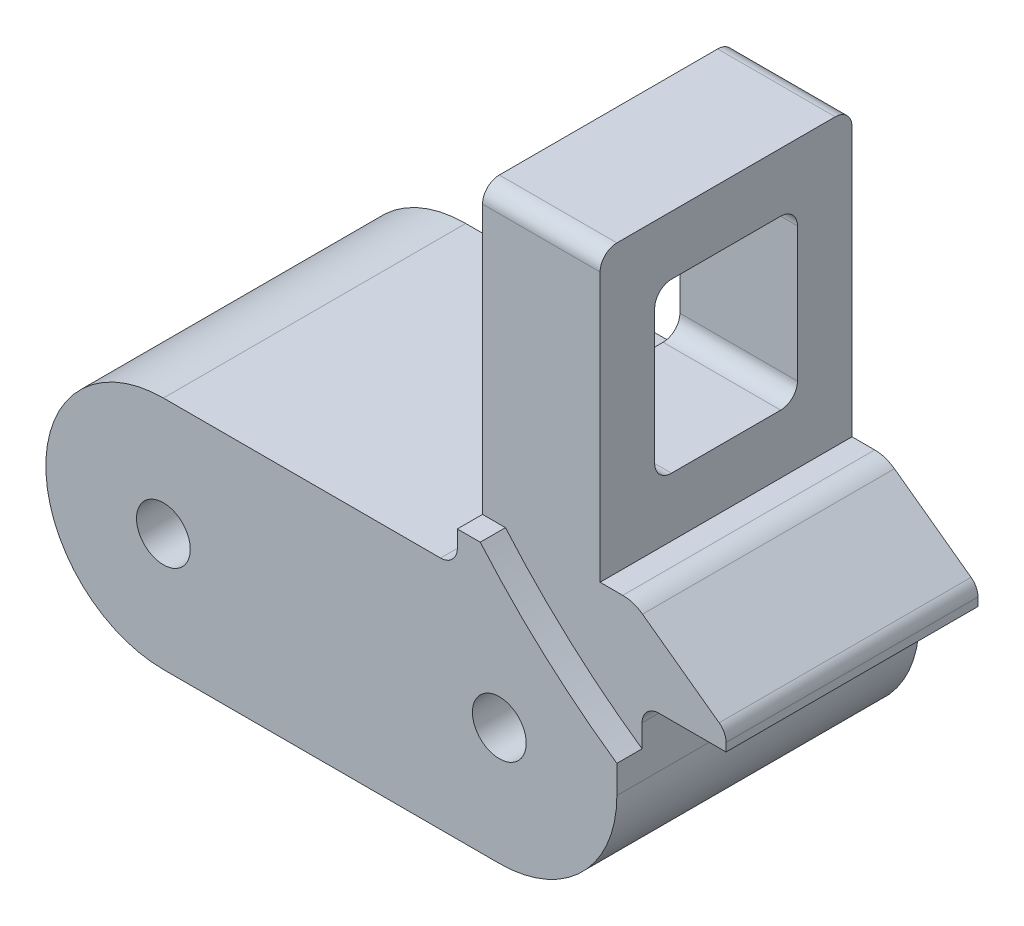
SolidWorks part; units mm, degrees
ref_plane "前视基准面" through (0, 0, 0) normal (0, 0, 1) x (1, 0, 0)
ref_plane "上视基准面" through (0, 0, 0) normal (0, 1, 0) x (1, 0, 0)
ref_plane "右视基准面" through (0, 0, 0) normal (1, 0, 0) x (0, 0, -1)
sketch "草图1" plane through (0, 0, 0) normal (0, 0, 1) x (1, 0, 0)
  line L0 (-20, 7) -> (-2.5, 7)
  line L1 (-20, -7) -> (0, -7)
  line L2 (-2.5, 7) -> (-2.5, 26)
  line L3 (-2.5, 26) -> (3.5, 26)
  line L4 (3.5, 26) -> (3.5, 9)
  line L5 (3.5, 9) -> (6.5, 9)
  line L6 (7, 4) -> (12, 4)
  line L7 (7, 0) -> (7, 4)
  line L8 (12, 4) -> (12, 5)
  line L9 (6.5, 9) -> (12, 5)
  circle A0 centre (0, 0) radius 1.6
  circle A1 centre (-20, 0) radius 1.6
  circle A2 centre (-20, 0) radius 7
  circle A3 centre (0, 0) radius 7
  dimension "D1" = 3.2
  dimension "D2" = 3.2
  dimension "D4" = 3.5
  dimension "D10" = 14
  dimension "D11" = 14
  dimension "D3" = 20
  dimension "D5" = 6
  dimension "D6" = 17
  dimension "D7" = 3
  dimension "D8" = 5
  dimension "D9" = 1
  dimension "D12" = 5
extrude "凸台-拉伸1" add sketch "草图1" along normal blind 14
fillet "圆角2" radius 1 2 edges at (7, 4, 7) (-2.5, 7, 7)
fillet "圆角4" radius 2 1 edges at (6.5, 9, 7)
fillet "圆角5" radius 1 1 edges at (12, 5, 7)
sketch "草图2" plane through (3.5, 0, 0) normal (1, 0, 0) x (0, 0, -1)
  line L0 (-7, 28.2067) -> (-7, 1.6741) construction
  line L1 (-12, 9) -> (-14, 9)
  line L2 (-14, 9) -> (0, 9) construction
  line L3 (-14, 9) -> (-14, 26)
  line L4 (-14, 26) -> (0, 26)
  line L5 (-12, 9) -> (-12, 25)
  line L6 (-12, 25) -> (-2, 25)
  line L7 (-2, 9) -> (0, 9)
  line L8 (-2, 9) -> (-2, 25)
  line L9 (0, 9) -> (0, 26)
  point P10 (-7, 25)
  point P16 (-7, 26)
  dimension "D1" = 1
  dimension "D2" = 10
extrude "切除-拉伸1" cut sketch "草图2" against normal blind 10
sketch "草图4" plane through (0, 0, 14) normal (0, 0, 1) x (1, 0, 0)
  line L1 (59.5, 65) -> (3.5, 65)
  line L2 (59.5, 65) -> (59.5, 9)
  line L3 (59.5, 9) -> (3.5, 9)
  line L4 (3.5, 65) -> (3.5, 9)
  line L5 (31.5, 9) -> (31.5, 65) construction
  line L6 (59.5, 37) -> (3.5, 37) construction
  circle A0 centre (31.5, 37) radius 43
  point P0 (31.5, 37)
  dimension "D1" = 56
  dimension "D2" = 56
extrude "切除-拉伸2" cut sketch "草图4" against normal blind 2
ref_plane "基准面1" through (0, 0, 7) normal (0, 0, 1) x (1, 0, 0)
mirror "镜向1" about plane through (0, 0, 7) normal (0, 0, 1) of "切除-拉伸2"
sketch "草图5" plane through (0, 0, 14) normal (0, 0, 1) x (1, 0, 0)
  line L5 (-1.1343, 9) -> (-2.5, 9)
  line L6 (-2.5, 9) -> (-2.5, 8)
  line L7 (-3.5, 7) -> (-20, 7)
  line L8 (-20, -7) -> (0, -7)
  line L9 (7, 0) -> (7, 1.6623)
  line L10 (-1.1343, 9) -> (-2.5, 9)
  line L11 (-2.5, 9) -> (-2.5, 8)
  line L12 (-3.5, 7) -> (-20, 7)
  line L13 (-20, -7) -> (0, -7)
  line L14 (7, 0) -> (7, 1.6623)
  circle A0 centre (0, 0) radius 1.6 construction
  circle A1 centre (-20, 0) radius 1.6 construction
  circle A2 centre (0, 0) radius 1.6
  circle A3 centre (-20, 0) radius 1.6
  arc A6 (-20, 7) -> (-20, -7) centre (-20, 0) ccw
  arc A7 (0, -7) -> (7, 0) centre (0, 0) ccw
  arc A10 (-20, 7) -> (-20, -7) centre (-20, 0) ccw
  arc A11 (0, -7) -> (7, 0) centre (0, 0) ccw
  arc A14 (-3.5, 7) -> (-2.5, 8) centre (-3.5, 8) ccw
  arc A15 (-3.5, 7) -> (-2.5, 8) centre (-3.5, 8) ccw
  arc A16 (-1.1343, 9) -> (7, 1.6623) centre (31.5, 37) ccw
  arc A24 (-1.1343, 9) -> (7, 1.6623) centre (31.5, 37) ccw
  dimension "D1" = 0
extrude "凸台-拉伸3" add sketch "草图5" along normal blind 2
sketch "草图6" plane through (0, 0, 0) normal (0, 0, -1) x (-1, 0, 0)
  line L5 (-7, 1.6623) -> (-7, 0)
  line L6 (0, -7) -> (20, -7)
  line L7 (20, 7) -> (3.5, 7)
  line L8 (2.5, 8) -> (2.5, 9)
  line L9 (2.5, 9) -> (1.1343, 9)
  line L10 (-7, 1.6623) -> (-7, 0)
  line L11 (0, -7) -> (20, -7)
  line L12 (20, 7) -> (3.5, 7)
  line L13 (2.5, 8) -> (2.5, 9)
  line L14 (2.5, 9) -> (1.1343, 9)
  circle A0 centre (20, 0) radius 1.6 construction
  circle A1 centre (0, 0) radius 1.6 construction
  circle A2 centre (20, 0) radius 1.6
  circle A3 centre (0, 0) radius 1.6
  arc A5 (-7, 0) -> (0, -7) centre (0, 0) ccw
  arc A6 (20, -7) -> (20, 7) centre (20, 0) ccw
  arc A9 (-7, 0) -> (0, -7) centre (0, 0) ccw
  arc A10 (20, -7) -> (20, 7) centre (20, 0) ccw
  arc A14 (2.5, 8) -> (3.5, 7) centre (3.5, 8) ccw
  arc A15 (2.5, 8) -> (3.5, 7) centre (3.5, 8) ccw
  arc A16 (-7, 1.6623) -> (1.1343, 9) centre (-31.5, 37) ccw
  arc A24 (-7, 1.6623) -> (1.1343, 9) centre (-31.5, 37) ccw
  dimension "D1" = 0
extrude "凸台-拉伸4" add sketch "草图6" along normal blind 2
sketch "草图8" plane through (0, 0, 12) normal (0, 0, 1) x (1, 0, 0)
  line L9 (-2.5, 9) -> (-1.1343, 9)
  line L10 (7, 1.6623) -> (7, 3)
  line L11 (8, 4) -> (12, 4)
  line L12 (12, 4) -> (12, 4.4908)
  line L13 (11.5882, 5.2995) -> (7.026, 8.6175)
  line L14 (5.8496, 9) -> (3.5, 9)
  line L15 (3.5, 9) -> (3.5, 25)
  line L16 (3.5, 25) -> (-2.5, 25)
  line L17 (-2.5, 25) -> (-2.5, 9)
  line L18 (-2.5, 9) -> (-1.1343, 9)
  line L19 (7, 1.6623) -> (7, 3)
  line L20 (8, 4) -> (12, 4)
  line L21 (12, 4) -> (12, 4.4908)
  line L22 (11.5882, 5.2995) -> (7.026, 8.6175)
  line L23 (5.8496, 9) -> (3.5, 9)
  line L24 (3.5, 9) -> (3.5, 25)
  line L25 (3.5, 25) -> (-2.5, 25)
  line L26 (-2.5, 25) -> (-2.5, 9)
  arc A4 (-1.1343, 9) -> (7, 1.6623) centre (31.5, 37) ccw
  arc A5 (8, 4) -> (7, 3) centre (8, 3) ccw
  arc A6 (12, 4.4908) -> (11.5882, 5.2995) centre (11, 4.4908) ccw
  arc A7 (7.026, 8.6175) -> (5.8496, 9) centre (5.8496, 7) ccw
  arc A8 (-1.1343, 9) -> (7, 1.6623) centre (31.5, 37) ccw
  arc A9 (8, 4) -> (7, 3) centre (8, 3) ccw
  arc A10 (12, 4.4908) -> (11.5882, 5.2995) centre (11, 4.4908) ccw
  arc A11 (7.026, 8.6175) -> (5.8496, 9) centre (5.8496, 7) ccw
  dimension "D1" = 0
extrude "凸台-拉伸6" add sketch "草图8" along normal blind 2.5
sketch "草图9" plane through (0, 0, 2) normal (0, 0, -1) x (-1, 0, 0)
  line L9 (-3.5, 25) -> (-3.5, 9)
  line L10 (-3.5, 9) -> (-5.8496, 9)
  line L11 (-7.026, 8.6175) -> (-11.5882, 5.2995)
  line L12 (-12, 4.4908) -> (-12, 4)
  line L13 (-12, 4) -> (-8, 4)
  line L14 (-7, 3) -> (-7, 1.6623)
  line L15 (1.1343, 9) -> (2.5, 9)
  line L16 (2.5, 9) -> (2.5, 25)
  line L17 (2.5, 25) -> (-3.5, 25)
  line L18 (-3.5, 25) -> (-3.5, 9)
  line L19 (-3.5, 9) -> (-5.8496, 9)
  line L20 (-7.026, 8.6175) -> (-11.5882, 5.2995)
  line L21 (-12, 4.4908) -> (-12, 4)
  line L22 (-12, 4) -> (-8, 4)
  line L23 (-7, 3) -> (-7, 1.6623)
  line L24 (1.1343, 9) -> (2.5, 9)
  line L25 (2.5, 9) -> (2.5, 25)
  line L26 (2.5, 25) -> (-3.5, 25)
  arc A4 (-5.8496, 9) -> (-7.026, 8.6175) centre (-5.8496, 7) ccw
  arc A5 (-11.5882, 5.2995) -> (-12, 4.4908) centre (-11, 4.4908) ccw
  arc A6 (-7, 3) -> (-8, 4) centre (-8, 3) ccw
  arc A7 (-7, 1.6623) -> (1.1343, 9) centre (-31.5, 37) ccw
  arc A8 (-5.8496, 9) -> (-7.026, 8.6175) centre (-5.8496, 7) ccw
  arc A9 (-11.5882, 5.2995) -> (-12, 4.4908) centre (-11, 4.4908) ccw
  arc A10 (-7, 3) -> (-8, 4) centre (-8, 3) ccw
  arc A11 (-7, 1.6623) -> (1.1343, 9) centre (-31.5, 37) ccw
  dimension "D1" = 0
extrude "凸台-拉伸7" add sketch "草图9" along normal blind 2.5
sketch "草图13" plane through (3.5, 0, 0) normal (1, 0, 0) x (0, 0, -1)
  line L0 (-14.5, 9) -> (0.5, 9) construction
  line L10 (-10.25, 22.5) -> (-3.75, 22.5)
  line L11 (-2.75, 21.5) -> (-2.75, 13.5)
  line L12 (-3.75, 12.5) -> (-10.25, 12.5)
  line L13 (-11.25, 13.5) -> (-11.25, 21.5)
  line L15 (-14.5, 9) -> (-14.5, 25) construction
  arc A6 (-10.25, 22.5) -> (-11.25, 21.5) centre (-10.25, 21.5) ccw
  arc A7 (-3.75, 22.5) -> (-2.75, 21.5) centre (-3.75, 21.5) cw
  arc A8 (-10.25, 12.5) -> (-11.25, 13.5) centre (-10.25, 13.5) cw
  arc A9 (-2.75, 13.5) -> (-3.75, 12.5) centre (-3.75, 13.5) cw
  point P8 (-11.25, 22.5)
  point P12 (-2.75, 22.5)
  point P16 (-11.25, 12.5)
  dimension "D5" = 1
  dimension "D6" = 1
  dimension "D7" = 1
  dimension "D8" = 1
  dimension "D1" = 10
  dimension "D2" = 3.5
  dimension "D3" = 3.25
  dimension "D4" = 8.5
extrude "切除-拉伸3" cut sketch "草图13" against normal through all
sketch "草图15" plane through (0, 25, 0) normal (0, 1, 0) x (1, 0, 0)
  line L4 (-2.5, 0.5) -> (-2.5, -14.5)
  line L5 (-2.5, -14.5) -> (3.5, -14.5)
  line L6 (3.5, -14.5) -> (3.5, 0.5)
  line L7 (3.5, 0.5) -> (-2.5, 0.5)
  line L8 (-2.5, 0.5) -> (-2.5, -14.5)
  line L9 (-2.5, -14.5) -> (3.5, -14.5)
  line L11 (3.5, 0.5) -> (-2.5, 0.5)
  line L14 (3.5, -14.5) -> (3.5, 0.5)
  dimension "D1" = 0
extrude "凸台-拉伸10" add sketch "草图15" along normal blind 1
sketch "草图14" plane through (3.5, 0, 0) normal (1, 0, 0) x (0, 0, -1)
  line L0 (-2.75, 13.5) -> (-2.75, 21.5) construction
  line L1 (-10.25, 12.5) -> (-3.75, 12.5) construction
  line L2 (-11.25, 21.5) -> (-11.25, 13.5) construction
  line L3 (-3.75, 22.5) -> (-10.25, 22.5) construction
  line L4 (-2.75, 13.5) -> (-2.75, 21.5)
  line L6 (0.5, 9) -> (0.5, 26)
  line L7 (0.5, 26) -> (-14.5, 26)
  line L8 (-14.5, 26) -> (-14.5, 9)
  line L9 (-14.5, 9) -> (0.5, 9)
  line L13 (-14.5, 26) -> (-14.5, 9)
  line L14 (-14.5, 9) -> (0.5, 9)
  line L15 (-10.25, 12.5) -> (-3.75, 12.5)
  line L16 (-11.25, 21.5) -> (-11.25, 13.5)
  line L17 (-3.75, 22.5) -> (-10.25, 22.5)
  line L21 (0.5, 9) -> (0.5, 26)
  line L24 (0.5, 26) -> (-14.5, 26)
  arc A0 (-2.75, 21.5) -> (-3.75, 22.5) centre (-3.75, 21.5) ccw construction
  arc A1 (-3.75, 12.5) -> (-2.75, 13.5) centre (-3.75, 13.5) ccw construction
  arc A2 (-11.25, 13.5) -> (-10.25, 12.5) centre (-10.25, 13.5) ccw construction
  arc A9 (-10.25, 22.5) -> (-11.25, 21.5) centre (-10.25, 21.5) ccw construction
  arc A10 (-2.75, 21.5) -> (-3.75, 22.5) centre (-3.75, 21.5) ccw
  arc A11 (-3.75, 12.5) -> (-2.75, 13.5) centre (-3.75, 13.5) ccw
  arc A12 (-11.25, 13.5) -> (-10.25, 12.5) centre (-10.25, 13.5) ccw
  arc A13 (-10.25, 22.5) -> (-11.25, 21.5) centre (-10.25, 21.5) ccw
  dimension "D1" = 0
extrude "凸台-拉伸9" add sketch "草图14" along normal blind 1
fillet "圆角6" radius 1 2 edges at (1, 26, -0.5) (1, 26, 14.5)
